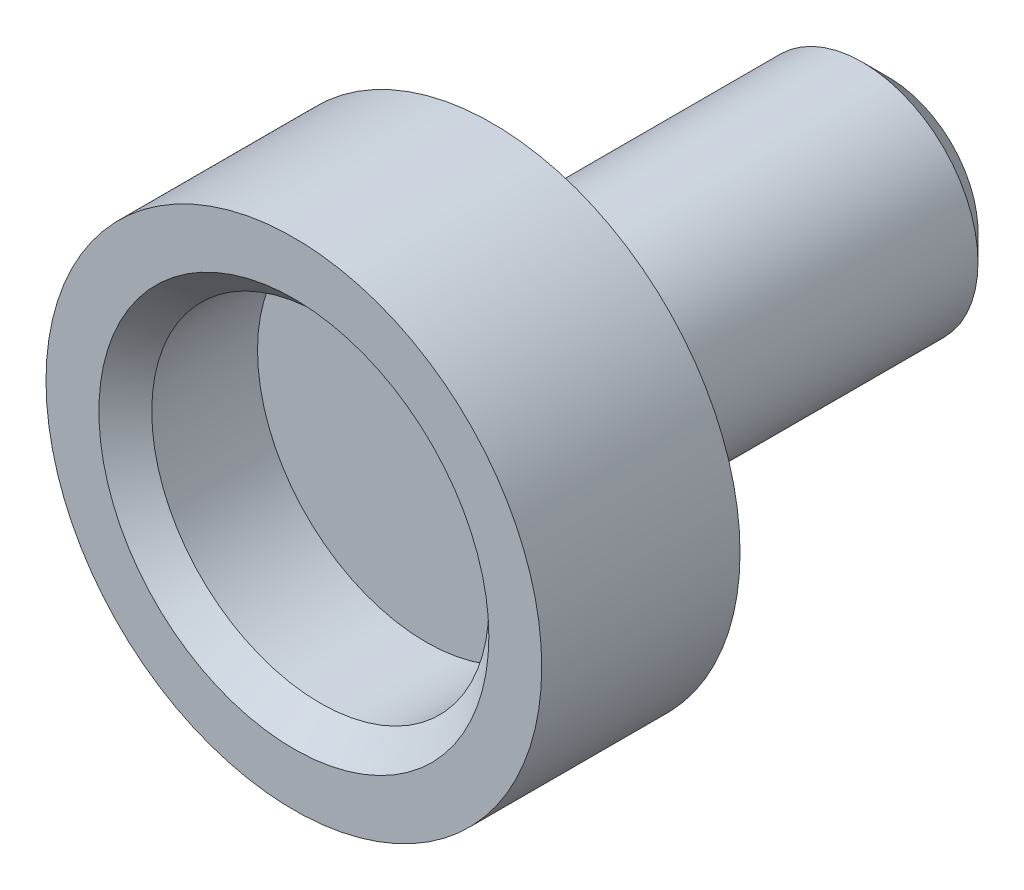
SolidWorks part; units mm, degrees
ref_plane "Plan de face" through (0, 0, 0) normal (0, 0, 1) x (1, 0, 0)
ref_plane "Plan de dessus" through (0, 0, 0) normal (0, 1, 0) x (1, 0, 0)
ref_plane "Plan de droite" through (0, 0, 0) normal (1, 0, 0) x (0, 0, -1)
sketch "Esquisse1" plane through (0, 0, 0) normal (0, 0, 1) x (1, 0, 0)
  circle A0 centre (0, 0) radius 2.55
  circle A1 centre (0, 0) radius 3.75
  dimension "D1" = 5.1
  dimension "D2" = 1.2
extrude "Boss.-Extru.1" add sketch "Esquisse1" along normal blind 2
sketch "Esquisse2" plane through (0, 0, 0) normal (0, 0, -1) x (-1, 0, 0)
  circle A1 centre (0, 0) radius 3.75
  circle A2 centre (0, 0) radius 3.75
  dimension "D1" = 0
extrude "Boss.-Extru.2" add sketch "Esquisse2" along normal blind 1
sketch "Esquisse3" plane through (0, 0, -1) normal (0, 0, -1) x (-1, 0, 0)
  circle A0 centre (0, 0) radius 1.75
  dimension "D1" = 3.5
extrude "Boss.-Extru.3" add sketch "Esquisse3" along normal blind 6
fillet "Congé1" radius 0.6 1 edges at (-1.75, 0, -1)
chamfer "Chanfrein1" distance 0.4 angle 45 1 edges at (-1.75, 0, -7)
chamfer "Chanfrein2" distance 0.4 angle 45 1 edges at (2.55, 0, 2)
